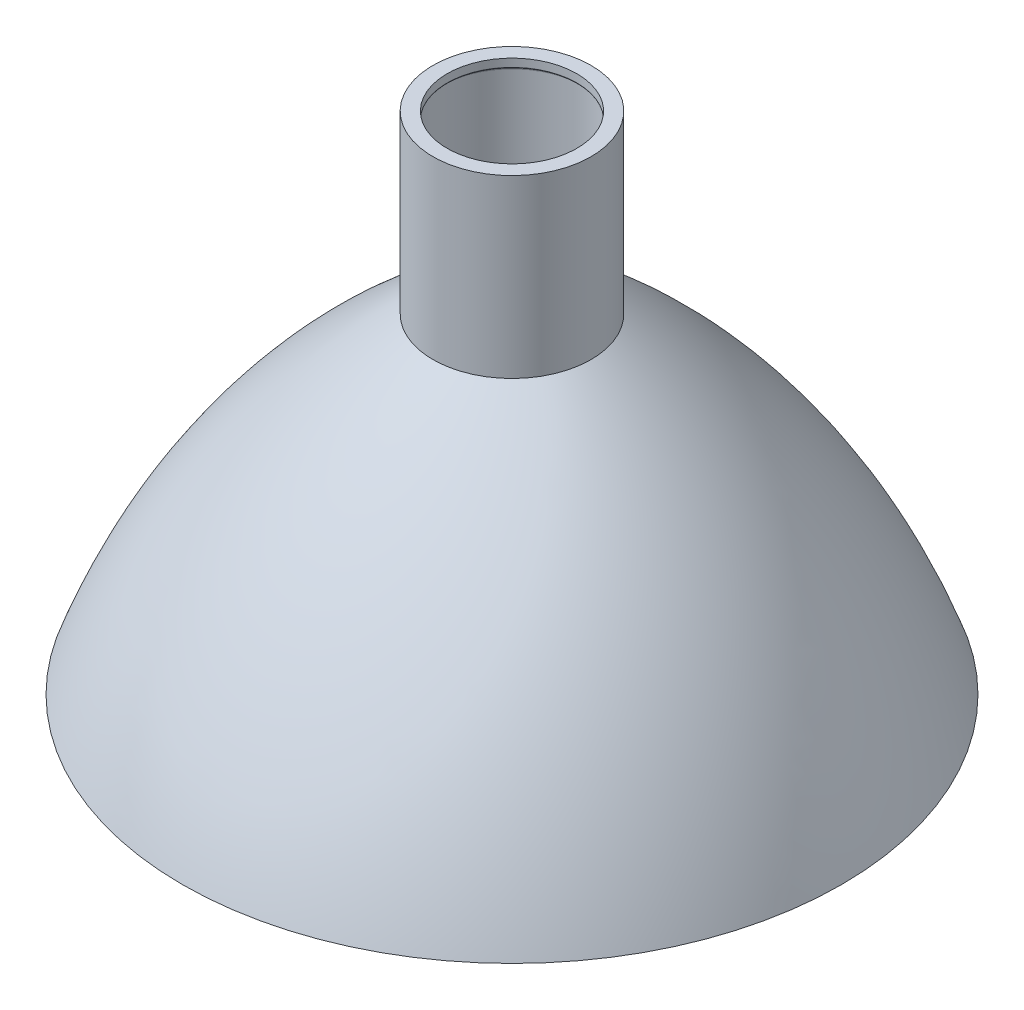
SolidWorks part; units mm, degrees
material "Alumina"
ref_plane "Front Plane" through (0, 0, 0) normal (0, 0, 1) x (1, 0, 0)
ref_plane "Top Plane" through (0, 0, 0) normal (0, 1, 0) x (1, 0, 0)
ref_plane "Right Plane" through (0, 0, 0) normal (1, 0, 0) x (0, 0, -1)
sketch "Sketch1" plane through (0, 0, 0) normal (0, 0, 1) x (1, 0, 0)
  line L0 (-75, 0) -> (75, 0)
  line L1 (0, 0) -> (0, 75)
  line L2 (-16, 75) -> (16, 75)
  line L3 (0, 75) -> (0, 115)
  line L4 (-11.5, 115) -> (11.5, 115)
  line L5 (-18, 115) -> (-14.75, 115)
  line L6 (18, 115) -> (14.75, 115)
  line L7 (-75, 0) -> (-73, 0)
  line L8 (14.75, 115) -> (14.75, 113.2)
  line L9 (-18, 75) -> (-18, 115)
  line L10 (-16, 75) -> (-16, 112)
  line L11 (-14.75, 115) -> (-14.75, 113.2)
  line L12 (-14.95, 113) -> (-15, 113)
  line L13 (14.95, 113) -> (15, 113)
  line L14 (16, 75) -> (16, 112)
  line L15 (18, 75) -> (18, 115)
  arc A0 (-15, 113) -> (-16, 112) centre (-15, 112) ccw
  arc A1 (-14.75, 113.2) -> (-14.95, 113) centre (-14.95, 113.2) cw
  arc A2 (14.75, 113.2) -> (14.95, 113) centre (14.95, 113.2) ccw
  arc A3 (15, 113) -> (16, 112) centre (15, 112) cw
  spline S0 degree 2 poles (-75, 0) (-58.4063, 46.597) (-18, 75) knots 0 0 0 1 1 1
  spline S1 degree 2 poles (-73, 0) (-55.204, 45.6046) (-16, 75) knots 0 0 0 1 1 1
  spline S2 degree 2 poles (75, 0) (58.4063, 46.597) (18, 75) knots 0 0 0 1 1 1
  spline S3 degree 2 poles (73, 0) (55.204, 45.6046) (16, 75) knots 0 0 0 1 1 1
  point P4 (0, 0)
  point P10 (0, 75)
  point P14 (0, 115)
  dimension "D1" = 1
  dimension "D2" = 0.2
revolve "Revolve1" add sketch "Sketch1" angle 360 about L1
